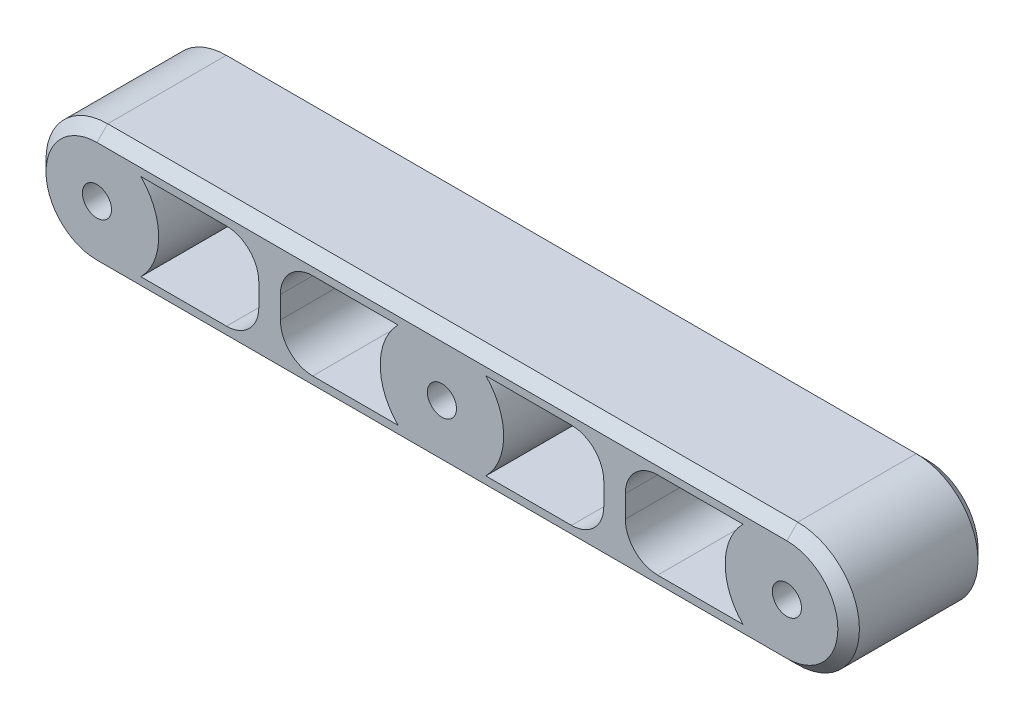
SolidWorks part; units mm, degrees
material "ABS"
ref_plane "前视基准面" through (0, 0, 0) normal (0, 0, 1) x (1, 0, 0)
ref_plane "上视基准面" through (0, 0, 0) normal (0, 1, 0) x (1, 0, 0)
ref_plane "右视基准面" through (0, 0, 0) normal (1, 0, 0) x (0, 0, -1)
other "Configuration Table"
sketch "草图1" plane through (0, 0, 0) normal (0, 0, 1) x (1, 0, 0)
  line L0 (0, 5.7257) -> (70, 5.7257) construction
  line L5 (35, 11.4514) -> (35, 0) construction
  line L6 (3, 5.7257) -> (3, 0) construction
  line L7 (3, 5.7257) -> (3, 11.4514) construction
  line L8 (67, 5.7257) -> (67, 0) construction
  line L9 (67, 0) -> (67, 11.4514) construction
  line L10 (3, 9.7514) -> (67, 9.7514) construction
  line L17 (3, 1.7) -> (67, 1.7) construction
  line L22 (3, 11.4514) -> (35, 11.4514)
  line L23 (35, 11.4514) -> (67, 11.4514)
  line L24 (35, 0) -> (67, 0)
  line L25 (3, 0) -> (35, 0)
  line L26 (19, 9.7514) -> (19, 1.7) construction
  line L27 (51.0134, 9.7514) -> (51.0134, 1.7) construction
  line L28 (7.0715, 9.7514) -> (18.0143, 9.7514)
  line L29 (18.0143, 9.7514) -> (20.0143, 9.7514) construction
  line L30 (18.0143, 9.7514) -> (18.0143, 1.7) construction
  line L31 (18.0143, 1.7) -> (20.0143, 1.7) construction
  line L32 (20.0143, 9.7514) -> (20.0143, 1.7) construction
  line L33 (19.0143, 1.7) -> (19.0143, 9.7514) construction
  line L34 (18.0143, 5.7257) -> (20.0143, 5.7257) construction
  line L35 (50.0134, 9.7514) -> (52.0134, 9.7514) construction
  line L36 (50.0134, 9.7514) -> (50.0134, 1.7) construction
  line L37 (50.0134, 1.7) -> (52.0134, 1.7) construction
  line L38 (52.0134, 9.7514) -> (52.0134, 1.7) construction
  line L39 (51.0134, 1.7) -> (51.0134, 9.7514) construction
  line L40 (50.0134, 5.7257) -> (52.0134, 5.7257) construction
  line L41 (18.0143, 9.7514) -> (18.0143, 1.7)
  line L42 (18.0143, 1.7) -> (7.0715, 1.7)
  line L43 (20.0143, 9.7514) -> (20.0143, 1.7)
  line L44 (20.0143, 1.7) -> (30.9285, 1.7)
  line L45 (20.0143, 9.7514) -> (30.9285, 9.7514)
  line L46 (39.0715, 9.7514) -> (50.0134, 9.7514)
  line L47 (50.0134, 9.7514) -> (50.0134, 1.7)
  line L48 (50.0134, 1.7) -> (39.0715, 1.7)
  line L49 (62.9285, 9.7514) -> (52.0134, 9.7514)
  line L50 (52.0134, 9.7514) -> (52.0134, 1.7)
  line L51 (52.0134, 1.7) -> (62.9285, 1.7)
  circle A0 centre (35, 5.7257) radius 1.35
  circle A1 centre (3, 5.7257) radius 1.35
  circle A2 centre (67, 5.7257) radius 1.35
  arc A3 (3, 9.7514) -> (3, 1.7) centre (3, 5.7257) cw construction
  arc A6 (67, 9.7514) -> (67, 1.7) centre (67, 5.7257) ccw construction
  circle A7 centre (35, 5.7257) radius 5.7257 construction
  arc A8 (30.9285, 9.7514) -> (30.9285, 1.7) centre (35, 5.7257) ccw
  arc A9 (39.0715, 9.7514) -> (39.0715, 1.7) centre (35, 5.7257) cw
  circle A10 centre (67, 5.7257) radius 5.7257 construction
  circle A11 centre (3, 5.7257) radius 5.7257 construction
  arc A12 (7.0715, 9.7514) -> (7.0715, 1.7) centre (3, 5.7257) cw
  arc A13 (62.9285, 9.7514) -> (62.9285, 1.7) centre (67, 5.7257) ccw
  arc A14 (3, 11.4514) -> (3, 0) centre (3, 5.7257) ccw
  arc A15 (67, 11.4514) -> (67, 0) centre (67, 5.7257) cw
  point P4 (19.0143, 5.7257)
  point P37 (51.0134, 5.7257)
  dimension "D3" = 2.7
  dimension "D4" = 2.7
  dimension "D5" = 2.7
  dimension "D2" = 2
  dimension "D6" = 32
  dimension "D7" = 32
  dimension "D8" = 1.7
  dimension "D9" = 2
  dimension "D10" = 1.7
extrude "凸台-拉伸3" add sketch "草图1" along normal blind 13
fillet "圆角1" radius 3 8 edges at (20.0143, 9.7514, 6.5) (18.0143, 9.7514, 6.5) (18.0143, 1.7, 6.5) (20.0143, 1.7, 6.5) (50.0134, 1.7, 6.5) (52.0134, 1.7, 6.5) (52.0134, 9.7514, 6.5) (50.0134, 9.7514, 6.5)
chamfer "倒角1" distance 1 angle 45 8 edges at (35, 0, 13) (35, 0, 0) (72.7257, 5.7257, 0) (-2.7257, 5.7257, 0) (35, 11.4514, 0) (72.7257, 5.7257, 13) (-2.7257, 5.7257, 13) (35, 11.4514, 13)
